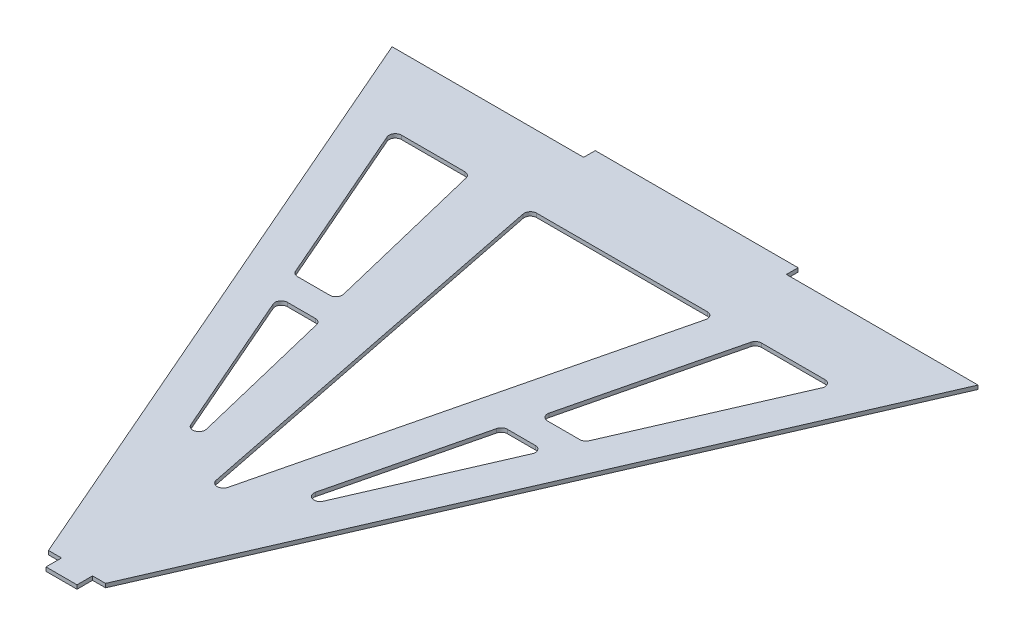
SolidWorks part; units mm, degrees
material "Balsa"
ref_plane "Front Plane" through (0, 0, 0) normal (0, 0, 1) x (1, 0, 0)
ref_plane "Top Plane" through (0, 0, 0) normal (0, 1, 0) x (1, 0, 0)
ref_plane "Right Plane" through (0, 0, 0) normal (1, 0, 0) x (0, 0, -1)
sketch "Sketch2" plane through (0, 0, 0) normal (0, 1, 0) x (1, 0, 0)
  line L0 (-122.047, 0) -> (0, 0)
  line L10 (-11.684, -253.746) -> (-6.35, -253.746)
  line L13 (-122.047, 0) -> (-11.684, -253.746)
  line L14 (0, 0) -> (122.047, 0)
  line L24 (11.684, -253.746) -> (6.35, -253.746)
  line L26 (-6.35, -253.746) -> (-6.35, -260.096)
  line L27 (-6.35, -260.096) -> (6.35, -260.096)
  line L28 (6.35, -260.096) -> (6.35, -253.746)
  line L30 (0, 0) -> (0, -520.192) construction
  line L32 (122.047, 0) -> (11.684, -253.746)
  line L34 (-60.706, -253.746) -> (138.5807, -253.746) construction
  point P2 (0, -260.096)
  dimension "D1" = 122.047
  dimension "D2" = 260.096
  dimension "D5" = 12.7
  dimension "D6" = 122.047
  dimension "D9" = 6.35
  dimension "D12" = 5.334
extrude "Boss-Extrude1" add sketch "Sketch2" along normal blind 1.5875
sketch "Sketch3" plane through (0, 1.5875, 0) normal (0, 1, 0) x (1, 0, 0)
  line L0 (41.529, 0) -> (41.529, -4.7625)
  line L1 (122.047, 0) -> (-122.047, 0) construction
  line L2 (41.529, -4.7625) -> (119.9756, -4.7625)
  line L3 (11.684, -253.746) -> (122.047, 0) construction
  line L4 (119.9756, -4.7625) -> (122.047, 0)
  line L5 (122.047, 0) -> (41.529, 0)
  line L6 (0, 0) -> (0, -404.1189) construction
  line L7 (-119.9756, -4.7625) -> (-122.047, 0)
  line L8 (-41.529, -4.7625) -> (-119.9756, -4.7625)
  line L9 (-41.529, 0) -> (-41.529, -4.7625)
  line L10 (-122.047, 0) -> (-41.529, 0)
  dimension "D1" = 80.518
  dimension "D2" = 4.7625
extrude "Cut-Extrude1" cut sketch "Sketch3" against normal through all
sketch "Sketch4" plane through (0, 1.5875, 0) normal (0, 1, 0) x (1, 0, 0)
  line L0 (0, 0) -> (0, -260.096) construction
  line L1 (-6.35, -260.096) -> (6.35, -260.096) construction
  line L2 (-107.1815, -34.1787) -> (107.1815, -34.1787) construction
  line L3 (-119.9756, -4.7625) -> (-11.684, -253.746) construction
  line L4 (11.684, -253.746) -> (119.9756, -4.7625) construction
  line L5 (41.7559, -34.1787) -> (-11.684, -253.746) construction
  line L6 (37.3265, -116.8217) -> (54.6181, -116.8217)
  line L7 (-34.4441, -34.1787) -> (11.7148, -253.6751) construction
  line L8 (54.6181, -116.8217) -> (15.3553, -207.0946)
  line L9 (-34.4441, -34.1787) -> (41.7559, -34.1787)
  line L10 (41.7559, -34.1787) -> (0, -205.7402)
  line L11 (0, -205.7402) -> (-34.4441, -34.1787)
  line L12 (58.7479, -34.1787) -> (90.5624, -34.1787)
  line L13 (90.5624, -34.1787) -> (59.4747, -105.6554)
  line L14 (59.4747, -105.6554) -> (41.3514, -105.6554)
  line L15 (41.3514, -105.6554) -> (58.7479, -34.1787)
  line L16 (15.3553, -207.0946) -> (37.3265, -116.8217)
  line L17 (-15.3553, -207.0946) -> (-37.3265, -116.8217)
  line L18 (-41.3514, -105.6554) -> (-58.7479, -34.1787)
  line L19 (-59.4747, -105.6554) -> (-41.3514, -105.6554)
  line L20 (-90.5624, -34.1787) -> (-59.4747, -105.6554)
  line L21 (-58.7479, -34.1787) -> (-90.5624, -34.1787)
  line L22 (-54.6181, -116.8217) -> (-15.3553, -207.0946)
  line L23 (-37.3265, -116.8217) -> (-54.6181, -116.8217)
  point P24 (13.8234, -209.7784)
  dimension "D1" = 76.2
  dimension "D2" = 31.8145
  dimension "D3" = 18.1234
  dimension "D4" = 17.2916
  dimension "D5" = 15.24
  dimension "D6" = 16.51
  dimension "D7" = 15.24
  dimension "D8" = 15.24
  dimension "D9" = 9.827
extrude "Cut-Extrude2" cut sketch "Sketch4" against normal up to surface (1.5875 mm away) contours L11 L9 L10 | L18 L21 L20 L19 | L15 L12 L13 L14 | L16 L6 L8 | L17 L23 L22 up to face at (0, 0, 129.5188)
fillet "Fillet1" radius 2.54 17 edges at (54.6181, 0.7937, 116.8217) (37.3265, 0.7937, 116.8217) (-37.3265, 0.7937, 116.8217) (-54.6181, 0.7937, 116.8217) (-15.3553, 0.7937, 207.0946) (41.3514, 0.7938, 105.6554) (15.3553, 0.7937, 207.0946) (-59.4747, 0.7938, 105.6554) (0, 0.7938, 205.7402) (-41.3514, 0.7937, 105.6554) (59.4747, 0.7937, 105.6554) (58.7479, 0.7937, 34.1787) (90.5624, 0.7938, 34.1787) (41.7559, 0.7937, 34.1787) (-34.4441, 0.7937, 34.1787) (-58.7479, 0.7937, 34.1787) (-90.5624, 0.7937, 34.1787)
